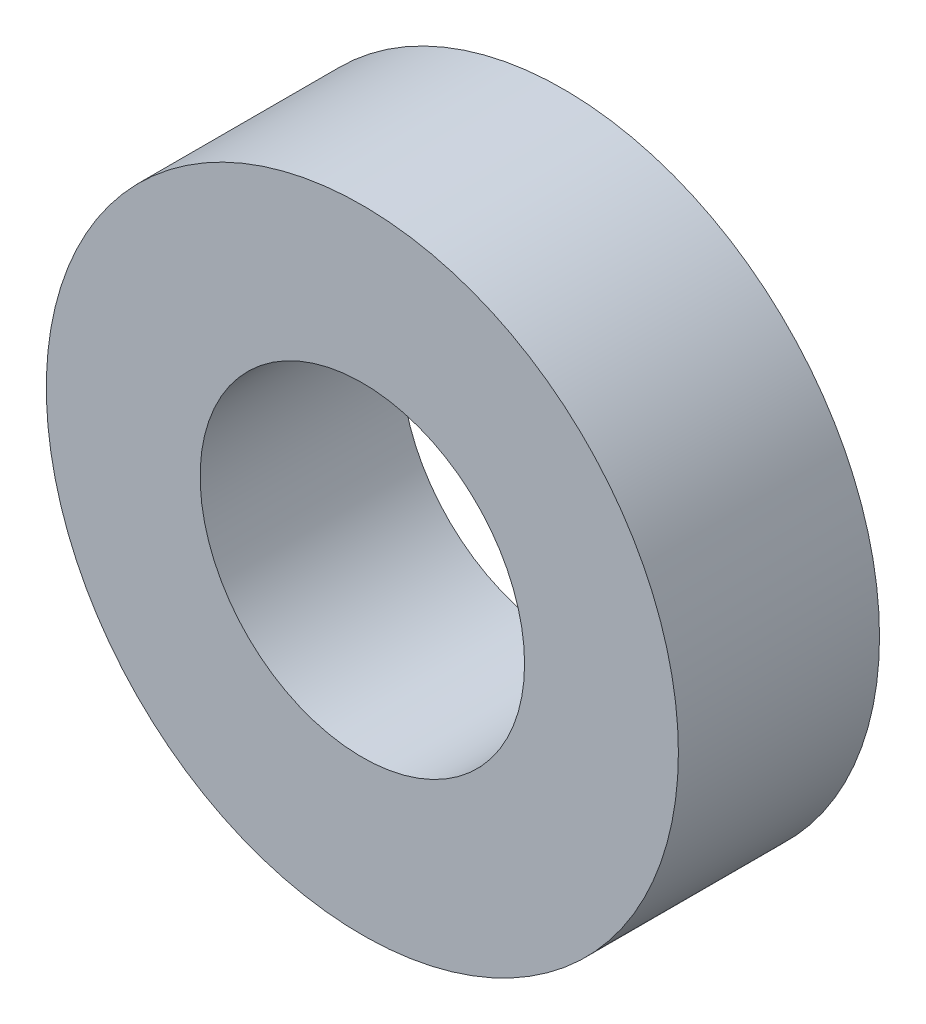
SolidWorks part; units mm, degrees
ref_plane "Alzado" through (0, 0, 0) normal (0, 0, 1) x (1, 0, 0)
ref_plane "Planta" through (0, 0, 0) normal (0, 1, 0) x (1, 0, 0)
ref_plane "Vista lateral" through (0, 0, 0) normal (1, 0, 0) x (0, 0, -1)
sketch "Croquis1" plane through (0, 0, 0) normal (0, 0, 1) x (1, 0, 0)
  circle A0 centre (0, 0) radius 11
  circle A1 centre (0, 0) radius 5.6463
  dimension "D1" = 22
extrude "Saliente-Extruir1" add sketch "Croquis1" along normal blind 7
